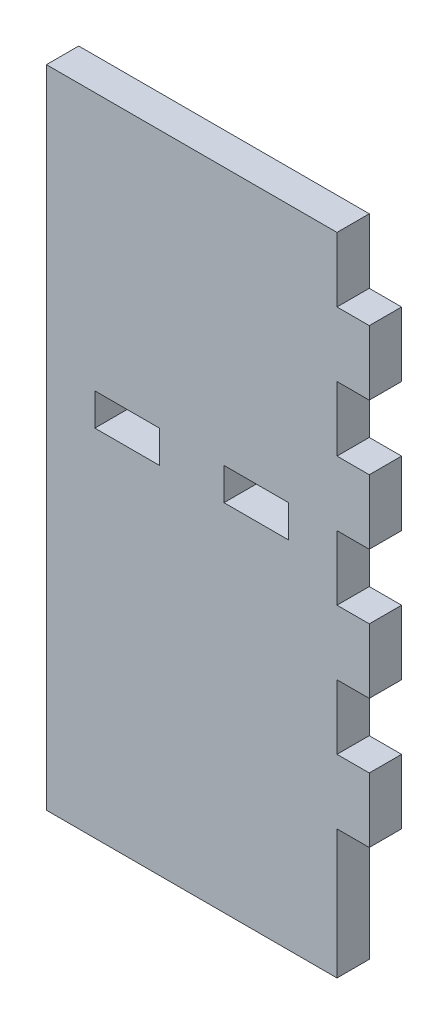
SolidWorks part; units mm, degrees
material "Pin"
ref_plane "Front" through (0, 0, 0) normal (0, 0, 1) x (1, 0, 0)
ref_plane "Top" through (0, 0, 0) normal (0, 1, 0) x (1, 0, 0)
ref_plane "Right" through (0, 0, 0) normal (1, 0, 0) x (0, 0, -1)
sketch "Esquisse1" plane through (0, 0, 0) normal (0, 0, 1) x (1, 0, 0)
  line L1 (-28.575, 63.5) -> (28.575, 63.5)
  line L2 (-28.575, 63.5) -> (-28.575, -63.5)
  line L3 (-28.575, -63.5) -> (28.575, -63.5)
  line L4 (28.575, 63.5) -> (28.575, -63.5)
  line L5 (-28.575, 63.5) -> (28.575, -63.5) construction
  line L6 (-28.575, -63.5) -> (28.575, 63.5) construction
  point P0 (0, 0)
  dimension "D1" = 127
  dimension "D2" = 57.15
extrude "Boss.-Extru.1" add sketch "Esquisse1" along normal blind 6.35
sketch "Esquisse2" plane through (0, 0, 6.35) normal (0, 0, 1) x (1, 0, 0)
  line L0 (28.575, -63.5) -> (28.575, 63.5) construction
  line L1 (28.575, 50.8) -> (34.925, 50.8)
  line L2 (28.575, 50.8) -> (28.575, 38.1)
  line L3 (28.575, 38.1) -> (34.925, 38.1)
  line L4 (34.925, 50.8) -> (34.925, 38.1)
  line L5 (28.575, 63.5) -> (-28.575, 63.5) construction
  dimension "D1" = 12.7
  dimension "D2" = 6.35
  dimension "D3" = 12.7
extrude "Boss.-Extru.2" add sketch "Esquisse2" against normal blind 6.35
pattern_linear "Répétition linéaire1" count 4 spacing 25.4 along (0, -1, 0) of "Boss.-Extru.2"
sketch "Esquisse3" plane through (0, 0, 6.35) normal (0, 0, 1) x (1, 0, 0)
  line L0 (-28.575, 63.5) -> (-28.575, -63.5) construction
  line L5 (-19.05, 12.7) -> (-6.35, 12.7)
  line L6 (-19.05, 12.7) -> (-19.05, 6.35)
  line L7 (-19.05, 6.35) -> (-6.35, 6.35)
  line L8 (-6.35, 12.7) -> (-6.35, 6.35)
  line L9 (28.575, 63.5) -> (-28.575, 63.5) construction
  dimension "D1" = 12.7
  dimension "D2" = 6.35
  dimension "D3" = 9.525
  dimension "D4" = 50.8
extrude "Enlèv. mat.-Extru.1" cut sketch "Esquisse3" against normal blind 6.35
pattern_linear "Répétition linéaire2" count 2 spacing 25.4 along (1, 0, 0) count 2 spacing 57.15 along (0, -1, 0) of "Enlèv. mat.-Extru.1"
